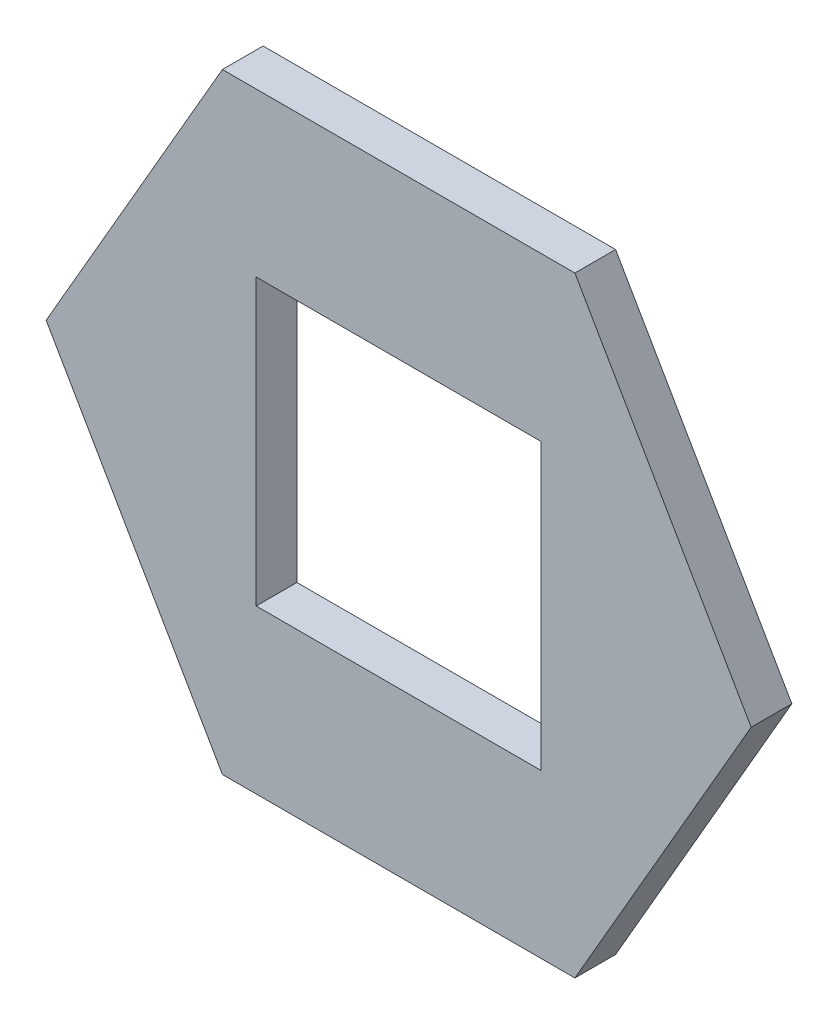
SolidWorks part; units mm, degrees
ref_plane "Front Plane" through (0, 0, 0) normal (0, 0, 1) x (1, 0, 0)
ref_plane "Top Plane" through (0, 0, 0) normal (0, 1, 0) x (1, 0, 0)
ref_plane "Right Plane" through (0, 0, 0) normal (1, 0, 0) x (0, 0, -1)
sketch "Sketch1" plane through (0, 0, 0) normal (0, 0, 1) x (1, 0, 0)
  line L1 (86.6025, 0) -> (43.3013, 75)
  line L2 (43.3013, 75) -> (-43.3013, 75)
  line L3 (-43.3013, 75) -> (-86.6025, 0)
  line L4 (-86.6025, 0) -> (-43.3013, -75)
  line L5 (-43.3013, -75) -> (43.3013, -75)
  line L6 (43.3013, -75) -> (86.6025, 0)
  circle A0 centre (0, 0) radius 75 construction
extrude "Cap" add sketch "Sketch1" along normal blind 10
sketch "Sketch2" plane through (0, 0, 10) normal (0, 0, 1) x (1, 0, 0)
  line L0 (-86.6025, 0) -> (-43.3013, -75) construction
  line L1 (-35, -35) -> (35, -35)
  line L2 (-35, -35) -> (-35, 35)
  line L3 (-35, 35) -> (35, 35)
  line L4 (35, -35) -> (35, 35)
  line L5 (-35, -35) -> (35, 35) construction
  line L6 (-35, 35) -> (35, -35) construction
  point P0 (0, 0)
  dimension "D1" = 70
  dimension "D2" = 60
extrude "Battery Access" cut sketch "Sketch2" against normal through all
